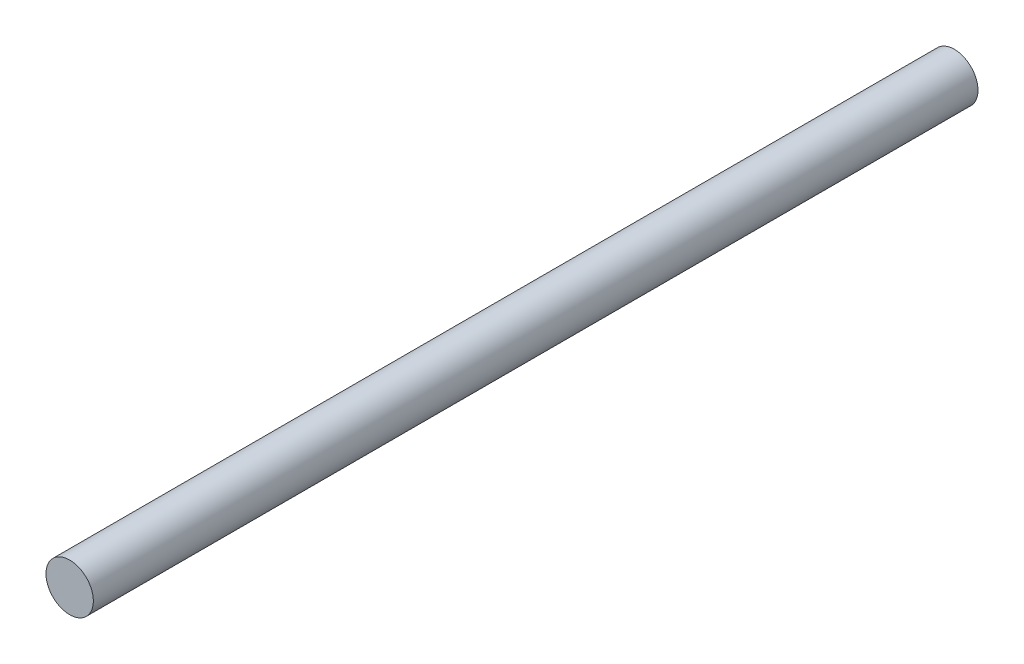
SolidWorks part; units mm, degrees
ref_plane "Front Plane" through (0, 0, 0) normal (0, 0, 1) x (1, 0, 0)
ref_plane "Top Plane" through (0, 0, 0) normal (0, 1, 0) x (1, 0, 0)
ref_plane "Right Plane" through (0, 0, 0) normal (1, 0, 0) x (0, 0, -1)
sketch "Sketch2" plane through (0, 0, 0) normal (0, 0, 1) x (1, 0, 0)
  circle A0 centre (0, 0) radius 15
  dimension "D1" = 30
extrude "Boss-Extrude1" add sketch "Sketch2" along normal blind 560
